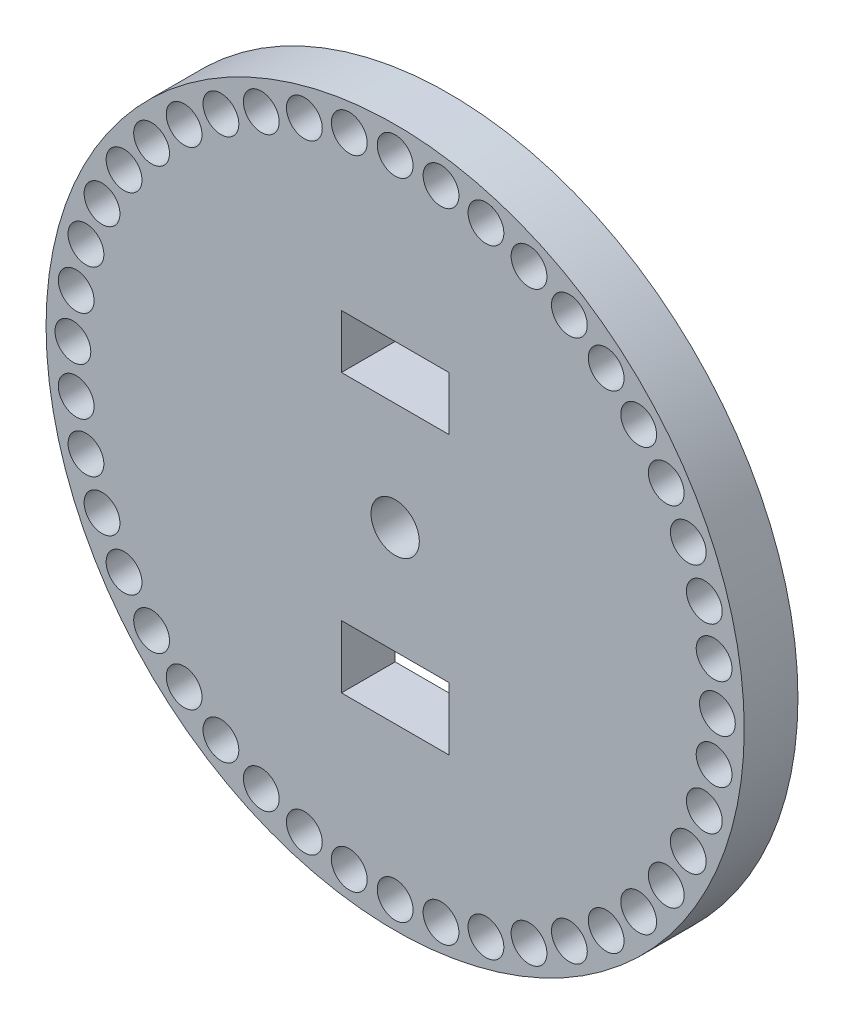
SolidWorks part; units mm, degrees
ref_plane "Front Plane" through (0, 0, 0) normal (0, 0, 1) x (1, 0, 0)
ref_plane "Top Plane" through (0, 0, 0) normal (0, 1, 0) x (1, 0, 0)
ref_plane "Right Plane" through (0, 0, 0) normal (1, 0, 0) x (0, 0, -1)
sketch "Sketch1" plane through (0, 0, 0) normal (0, 0, 1) x (1, 0, 0)
  line L0 (0, 0) -> (0, 9.75) construction
  circle A0 centre (0, 0) radius 19.5
  point P8 (0, 8.25)
  dimension "D1" = 39
extrude "Boss-Extrude1" add sketch "Sketch1" along normal blind 3
sketch "Sketch6" plane through (0, 0, 3) normal (0, 0, 1) x (1, 0, 0)
  line L0 (0, 0) -> (0, 18) construction
  circle A0 centre (0, 18) radius 1
  circle A1 centre (2.5617, 17.8168) radius 1
  circle A2 centre (5.0712, 17.2709) radius 1
  circle A3 centre (7.4775, 16.3734) radius 1
  circle A4 centre (9.7315, 15.1426) radius 1
  circle A5 centre (11.7875, 13.6035) radius 1
  circle A6 centre (13.6035, 11.7875) radius 1
  circle A7 centre (15.1426, 9.7315) radius 1
  circle A8 centre (16.3734, 7.4775) radius 1
  circle A9 centre (17.2709, 5.0712) radius 1
  circle A10 centre (17.8168, 2.5617) radius 1
  circle A11 centre (18, 0) radius 1
  circle A12 centre (17.8168, -2.5617) radius 1
  circle A13 centre (17.2709, -5.0712) radius 1
  circle A14 centre (16.3734, -7.4775) radius 1
  circle A15 centre (15.1426, -9.7315) radius 1
  circle A16 centre (13.6035, -11.7875) radius 1
  circle A17 centre (11.7875, -13.6035) radius 1
  circle A18 centre (9.7315, -15.1426) radius 1
  circle A19 centre (7.4775, -16.3734) radius 1
  circle A20 centre (5.0712, -17.2709) radius 1
  circle A21 centre (2.5617, -17.8168) radius 1
  circle A22 centre (0, -18) radius 1
  circle A23 centre (-2.5617, -17.8168) radius 1
  circle A24 centre (-5.0712, -17.2709) radius 1
  circle A25 centre (-7.4775, -16.3734) radius 1
  circle A26 centre (-9.7315, -15.1426) radius 1
  circle A27 centre (-11.7875, -13.6035) radius 1
  circle A28 centre (-13.6035, -11.7875) radius 1
  circle A29 centre (-15.1426, -9.7315) radius 1
  circle A30 centre (-16.3734, -7.4775) radius 1
  circle A31 centre (-17.2709, -5.0712) radius 1
  circle A32 centre (-17.8168, -2.5617) radius 1
  circle A33 centre (-18, 0) radius 1
  circle A34 centre (-17.8168, 2.5617) radius 1
  circle A35 centre (-17.2709, 5.0712) radius 1
  circle A36 centre (-16.3734, 7.4775) radius 1
  circle A37 centre (-15.1426, 9.7315) radius 1
  circle A38 centre (-13.6035, 11.7875) radius 1
  circle A39 centre (-11.7875, 13.6035) radius 1
  circle A40 centre (-9.7315, 15.1426) radius 1
  circle A41 centre (-7.4775, 16.3734) radius 1
  circle A42 centre (-5.0712, 17.2709) radius 1
  circle A43 centre (-2.5617, 17.8168) radius 1
  dimension "D2" = 2
  dimension "D1" = 18
  dimension "D3" = 44
extrude "Cut-Extrude3" cut sketch "Sketch6" against normal up to surface (3 mm away) contours A0
sketch "Sketch7" plane through (0, 0, 3) normal (0, 0, 1) x (1, 0, 0)
  circle A0 centre (0, 0) radius 1.35
  dimension "D1" = 2.7
extrude "Cut-Extrude4" cut sketch "Sketch7" against normal up to surface (3 mm away) up to face at (-16.8168, -2.5617, 0)
sketch "Sketch10" plane through (0, 0, 3) normal (0, 0, 1) x (1, 0, 0)
  line L0 (0, 0) -> (0, 9) construction
  line L1 (3, 9) -> (-3, 9)
  line L2 (-3, 9) -> (-3, 6)
  line L3 (-3, 6) -> (3, 6)
  line L4 (3, 9) -> (3, 6)
  line L5 (0, 0) -> (0, -15.6165) construction
  line L8 (-3, -6) -> (3, -6)
  line L9 (-3, -6) -> (-3, -9.5)
  line L10 (-3, -9.5) -> (3, -9.5)
  line L11 (3, -6) -> (3, -9.5)
  line L12 (-3, -6) -> (3, -9.5) construction
  line L13 (-3, -9.5) -> (3, -6) construction
  point P6 (0, -7.75)
  point P8 (0, 6)
  dimension "D1" = 3
  dimension "D2" = 3
  dimension "D3" = 9
  dimension "D4" = 6
  dimension "D5" = 3.5
  dimension "D6" = 6
extrude "Cut-Extrude5" cut sketch "Sketch10" against normal up to surface (3 mm away) up to face at (1.35, 0, 0)
